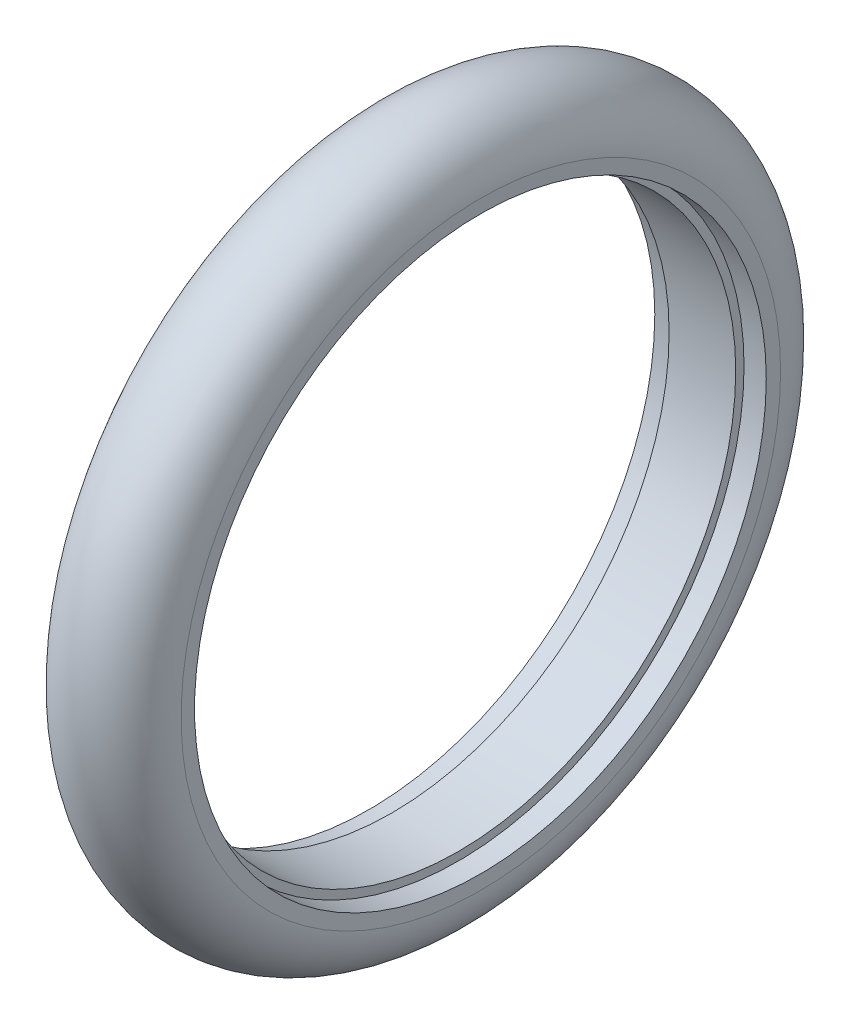
SolidWorks part; units mm, degrees
material "POLYURETHANE (11671)"
ref_plane "Front Plane" through (0, 0, 0) normal (0, 0, 1) x (1, 0, 0)
ref_plane "Top Plane" through (0, 0, 0) normal (0, 1, 0) x (1, 0, 0)
ref_plane "Right Plane" through (0, 0, 0) normal (1, 0, 0) x (0, 0, -1)
ref_axis "Axis1" through (88.99, 0, 0) along (-1, 0, 0)
sketch "Sketch1" plane through (0, 0, 0) normal (0, 0, 1) x (1, 0, 0)
  line L0 (0, 0) -> (0, 128.1625) construction
  line L1 (20.1625, 108) -> (20, 103)
  line L2 (-20.1625, 108) -> (-20.1625, 103)
  line L3 (20, 103) -> (12, 103)
  line L4 (-20.1625, 103) -> (-12, 103)
  line L5 (12, 103) -> (12, 100)
  line L6 (-12, 103) -> (-12, 100)
  line L7 (12, 100) -> (-12, 100)
  line L8 (88.99, 0) -> (-88.99, 0) construction
  line L9 (12, 100) -> (12, -100) construction
  line L20 (-20.1625, -103) -> (-20.1625, 103) construction
  line L39 (20, 103) -> (20, -103) construction
  line L40 (20, 103) -> (12, 103) construction
  arc A0 (20.1625, 108) -> (-20.1625, 108) centre (0, 108) ccw
  point P5 (-20.1625, 108)
  point P6 (20.1625, 108)
  point P15 (0, 100)
  point P17 (0, 125.8192)
  point P18 (0, 163.1382)
  point P19 (-11.0103, 111.4444)
  point P22 (0, 0)
  point P23 (0, 0)
  point P24 (0, 129.9947)
  point P25 (-20.1625, 104.1724)
  point P26 (-12, 103.5239)
  point P27 (0, 0)
  point P31 (0, 0)
  point P32 (15.1625, 111)
  point P33 (15.2835, 108)
  point P34 (0, 0)
  point P35 (15.1625, 111.9802)
  point P36 (15.2835, 110.6739)
  point P37 (15.1625, 108)
  point P38 (20.1625, 108.8522)
  point P39 (0, 0)
  point P40 (15.1625, 106.7153)
  point P41 (0, 0)
  point P42 (20.1625, 103)
  point P43 (20.1625, 103)
  point P44 (20.1625, 111.3243)
  point P45 (-20.1625, 110.2248)
  point P46 (16.5062, 103)
  point P49 (20.1625, 108)
  point P51 (20, 103)
  point P52 (20, 103)
  point P55 (20.1625, 108)
  point P56 (12, 103)
  point P57 (-20.1625, 104.1884)
  point P58 (20.1625, 103)
  point P61 (0, 0)
  dimension "D1" = 100
revolve "Revolve1" add sketch "Sketch1" angle 360 about axis through (88.99, 0, 0) along (-1, 0, 0)
